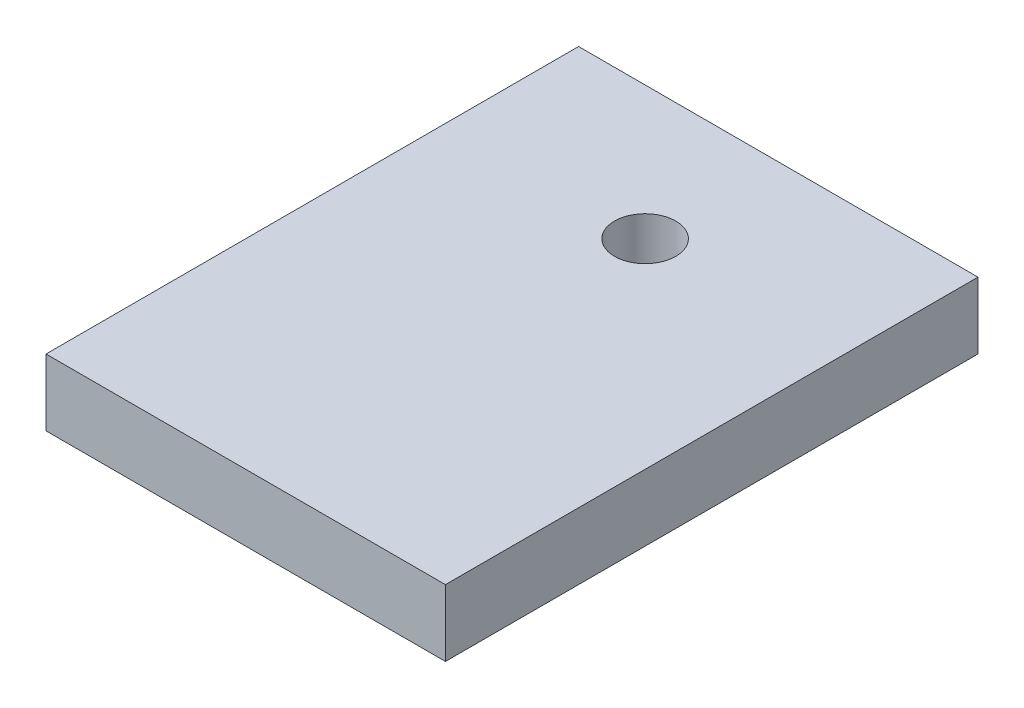
SolidWorks part; units mm, degrees
ref_plane "Front Plane" through (0, 0, 0) normal (0, 0, 1) x (1, 0, 0)
ref_plane "Top Plane" through (0, 0, 0) normal (0, 1, 0) x (1, 0, 0)
ref_plane "Right Plane" through (0, 0, 0) normal (1, 0, 0) x (0, 0, -1)
sketch "Sketch1" plane through (0, 0, 0) normal (0, 1, 0) x (1, 0, 0)
  line L1 (0, 0) -> (19.05, 0)
  line L2 (0, 0) -> (0, 25.4)
  line L3 (0, 25.4) -> (19.05, 25.4)
  line L4 (19.05, 0) -> (19.05, 25.4)
  circle A0 centre (9.525, 19.05) radius 1.4605
  point P7 (0, 0)
  point P8 (0, 0)
  dimension "D3" = 2.921
  dimension "D1" = 19.05
  dimension "D2" = 25.4
  dimension "D4" = 6.35
  dimension "D5" = 9.525
extrude "Boss-Extrude1" add sketch "Sketch1" along normal blind 3.175
